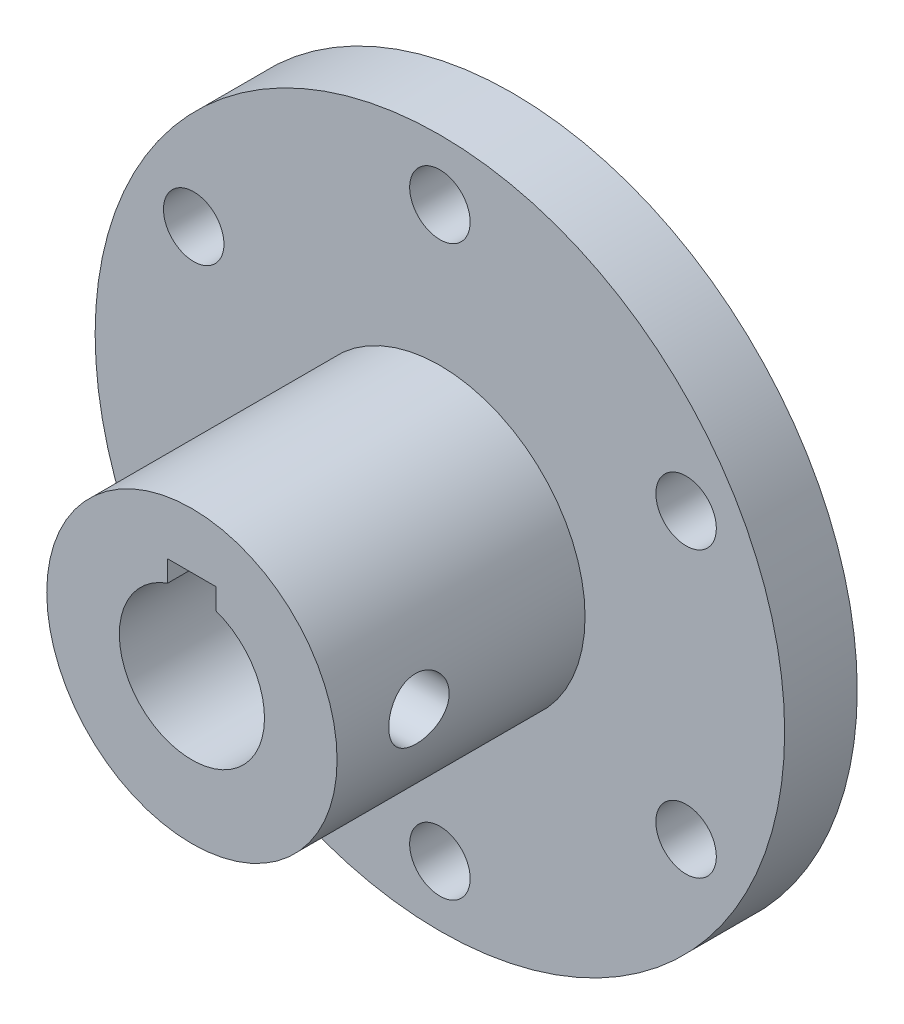
SolidWorks part; units mm, degrees
material "6061 合金"
ref_plane "正面" through (0, 0, 0) normal (0, 0, 1) x (1, 0, 0)
ref_plane "平面" through (0, 0, 0) normal (0, 1, 0) x (1, 0, 0)
ref_plane "右側面" through (0, 0, 0) normal (1, 0, 0) x (0, 0, -1)
sketch "ｽｹｯﾁ1" plane through (0, 0, 0) normal (0, 0, 1) x (1, 0, 0)
  circle A0 centre (0, 0) radius 28.5
  circle A1 centre (0, 0) radius 6
  dimension "D1" = 57
  dimension "D2" = 12
extrude "ﾎﾞｽ - 押し出し1" add sketch "ｽｹｯﾁ1" along normal blind 6
sketch "ｽｹｯﾁ2" plane through (0, 0, 6) normal (0, 0, 1) x (1, 0, 0)
  circle A0 centre (0, 0) radius 12
  circle A1 centre (0, 0) radius 6
  dimension "D1" = 24
extrude "ﾎﾞｽ - 押し出し2" add sketch "ｽｹｯﾁ2" along normal blind 20.5
hole_wizard "1/4 すきま穴1" positions "3Dｽｹｯﾁ1" profile "ｽｹｯﾁ4" hole size "1/4" standard "Ansi Inch"
sketch3d "3Dｽｹｯﾁ1"
  point P0 (11.999, 0.152, 19.7283)
sketch "ｽｹｯﾁ4" plane through (11.999, 0.152, 19.7283) normal (0, 0, 1) x (-0.0127, 0.9999, 0)
  line L0 (0, 0) -> (0, 10)
  line L1 (0, 10) -> (2.5, 10)
  line L2 (2.5, 10) -> (2.5, 0)
  line L5 (2.5, 0) -> (0, 0)
  line L10 (0, 10) -> (-2.5, 10) construction
  line L11 (0, -6.35) -> (0, 107.95) construction
  dimension "穴の直径" = 5
  dimension "穴の深さ" = 10
  dimension "ﾄﾞﾘﾙ角度" = 180
sketch "ｽｹｯﾁ5" plane through (0, 0, 6) normal (0, 0, 1) x (1, 0, 0)
  line L1 (0, 23.5) -> (-20.3516, 11.75)
  line L2 (-20.3516, 11.75) -> (-20.3516, -11.75)
  line L3 (-20.3516, -11.75) -> (0, -23.5)
  line L4 (0, -23.5) -> (20.3516, -11.75)
  line L5 (20.3516, -11.75) -> (20.3516, 11.75)
  line L6 (20.3516, 11.75) -> (0, 23.5)
  circle A0 centre (0, 0) radius 20.3516 construction
  circle A1 centre (0, 23.5) radius 2.5
  circle A2 centre (20.3516, 11.75) radius 2.5
  circle A3 centre (20.3516, -11.75) radius 2.5
  circle A4 centre (0, -23.5) radius 2.5
  circle A5 centre (-20.3516, -11.75) radius 2.5
  circle A6 centre (-20.3516, 11.75) radius 2.5
  point P23 (0, 0)
  dimension "D2" = 5
  dimension "D1" = 23.5
  dimension "D3" = 6
extrude "ｶｯﾄ - 押し出し1" cut sketch "ｽｹｯﾁ5" against normal blind 30 contours L1 A6 L2 | L2 A6 L1 | L5 A2 L6 | L6 A2 L5 | A1 | A5 | A4 | A3
sketch "ｽｹｯﾁ6" plane through (0, 0, 26.5) normal (0, 0, 1) x (1, 0, 0)
  line L0 (0, 0) -> (0, 1.4381) construction
  line L1 (0, 12) -> (0, 0) construction
  line L2 (-2, 5.6569) -> (-2, 7.4)
  line L3 (-2, 7.4) -> (2, 7.4)
  line L4 (2, 7.4) -> (2, 5.6569)
  circle A0 centre (0, 0) radius 12 construction
  circle A1 centre (0, 0) radius 6 construction
  circle A2 centre (0, 0) radius 6
  circle M5 centre (0, 0) radius 6
  dimension "D1" = 4
  dimension "D2" = 2
  dimension "D3" = 7.4
extrude "ｶｯﾄ - 押し出し2" cut sketch "ｽｹｯﾁ6" against normal blind 100 contours L4 L3 L2 M5
